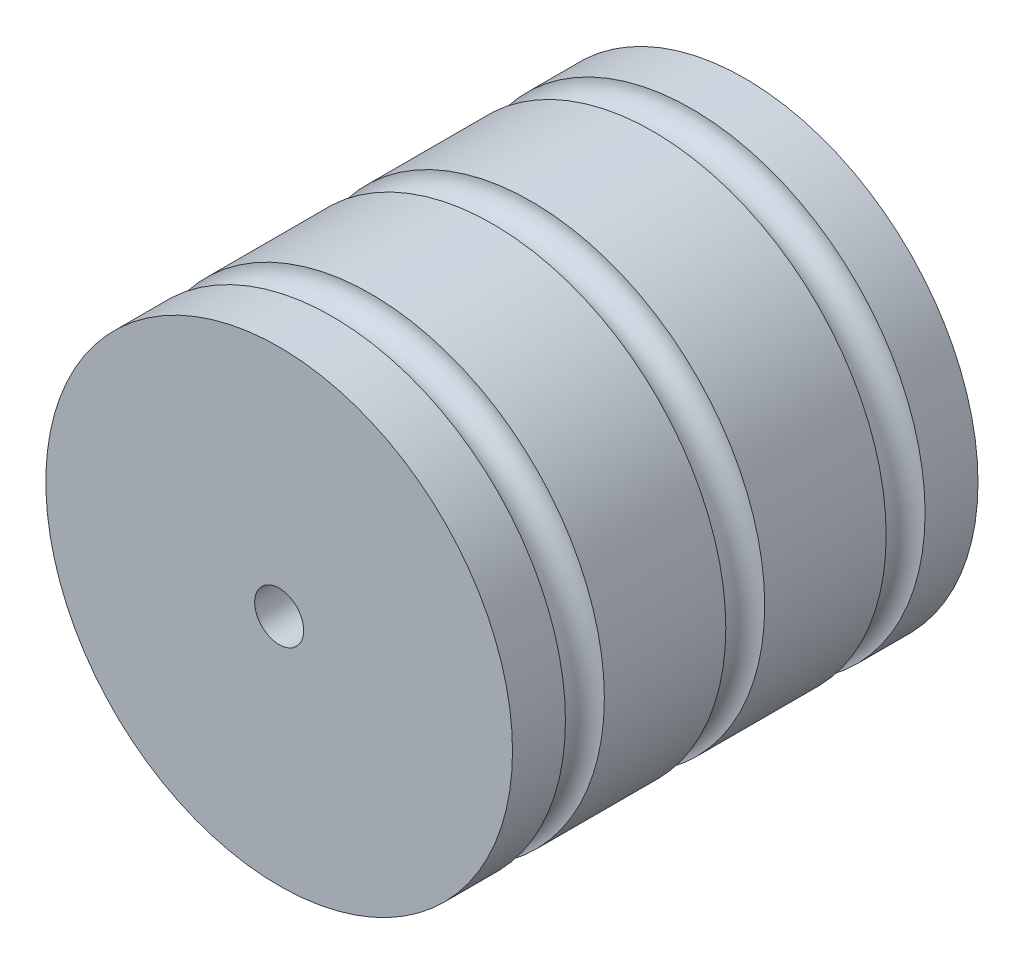
SolidWorks part; units mm, degrees
ref_plane "Front Plane" through (0, 0, 0) normal (0, 0, 1) x (1, 0, 0)
ref_plane "Top Plane" through (0, 0, 0) normal (0, 1, 0) x (1, 0, 0)
ref_plane "Right Plane" through (0, 0, 0) normal (1, 0, 0) x (0, 0, -1)
sketch "Sketch1" plane through (0, 0, 0) normal (0, 1, 0) x (1, 0, 0)
  line L1 (4, 0) -> (38.1, 0)
  line L2 (0, 0) -> (0, 76) construction
  line L3 (4, 76) -> (38.1, 76)
  line L8 (38.1, 0) -> (38.1, 8.6422)
  line L9 (38.1, 14.9922) -> (38.1, 34.825)
  line L10 (38.1, 41.175) -> (38.1, 61.0078)
  line L11 (38.1, 67.3578) -> (38.1, 76)
  line L12 (4, 76) -> (4, 0)
  arc A10 (38.1, 41.175) -> (38.1, 34.825) centre (38.1, 38) ccw
  arc A11 (38.1, 67.3578) -> (38.1, 61.0078) centre (38.1, 64.1828) ccw
  arc A12 (38.1, 14.9922) -> (38.1, 8.6422) centre (38.1, 11.8172) ccw
  dimension "D3" = 6.35
  dimension "D4" = 4
  dimension "D1" = 76
  dimension "D2" = 38.1
revolve "Revolve1" add sketch "Sketch1" angle 360 about L2
